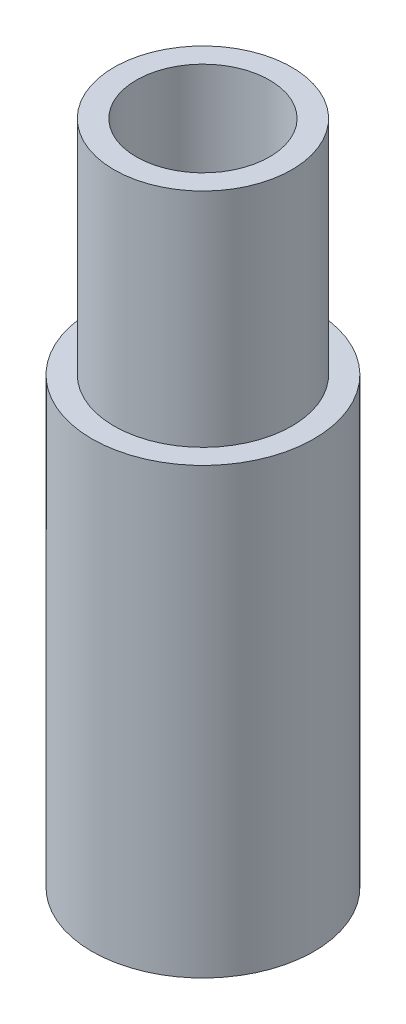
SolidWorks part; units mm, degrees
material "钴"
ref_plane "前视基准面" through (0, 0, 0) normal (0, 0, 1) x (1, 0, 0)
ref_plane "上视基准面" through (0, 0, 0) normal (0, 1, 0) x (1, 0, 0)
ref_plane "右视基准面" through (0, 0, 0) normal (1, 0, 0) x (0, 0, -1)
sketch "草图1" plane through (0, 0, 0) normal (0, 1, 0) x (1, 0, 0)
  circle A0 centre (0, 0) radius 5
extrude "凸台-拉伸1" add sketch "草图1" along normal blind 20
sketch "草图2" plane through (0, 20, 0) normal (0, 1, 0) x (1, 0, 0)
  circle A0 centre (0, 0) radius 4.0035
extrude "凸台-拉伸2" add sketch "草图2" along normal blind 10
sketch "草图3" plane through (0, 30, 0) normal (0, 1, 0) x (1, 0, 0)
  circle A0 centre (0, 0) radius 3
extrude "切除-拉伸1" cut sketch "草图3" against normal up to surface (10 mm away) up to face at (0, 20, 4.0035)
